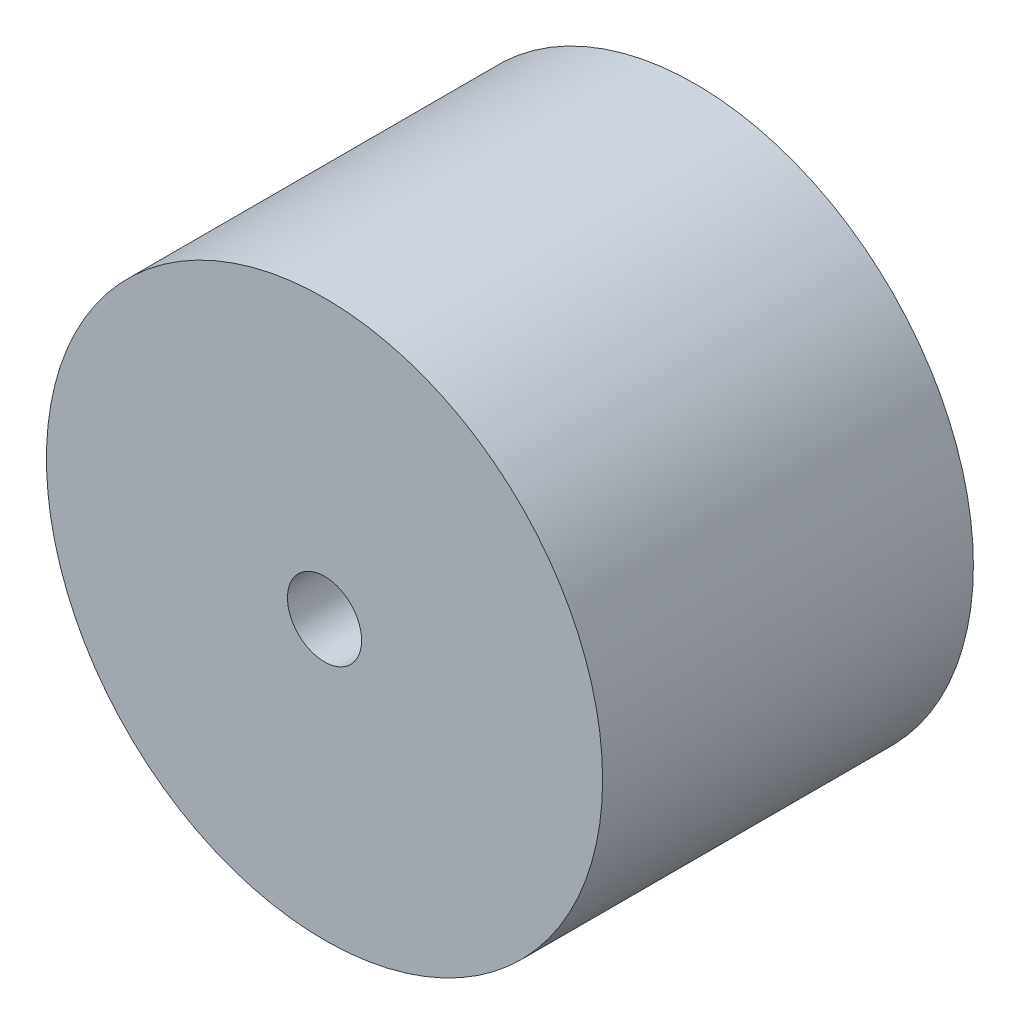
SolidWorks part; units mm, degrees
ref_plane "前视基准面" through (0, 0, 0) normal (0, 0, 1) x (1, 0, 0)
ref_plane "上视基准面" through (0, 0, 0) normal (0, 1, 0) x (1, 0, 0)
ref_plane "右视基准面" through (0, 0, 0) normal (1, 0, 0) x (0, 0, -1)
other "Configuration Table"
sketch "草图1" plane through (0, 0, 0) normal (0, 0, 1) x (1, 0, 0)
  circle A0 centre (0, 0) radius 15
  circle A1 centre (0, 0) radius 2
extrude "凸台-拉伸1" add sketch "草图1" along normal blind 20
sketch3d "3D草图1"
  point P0 (5.9827, 2.6832, 0)
